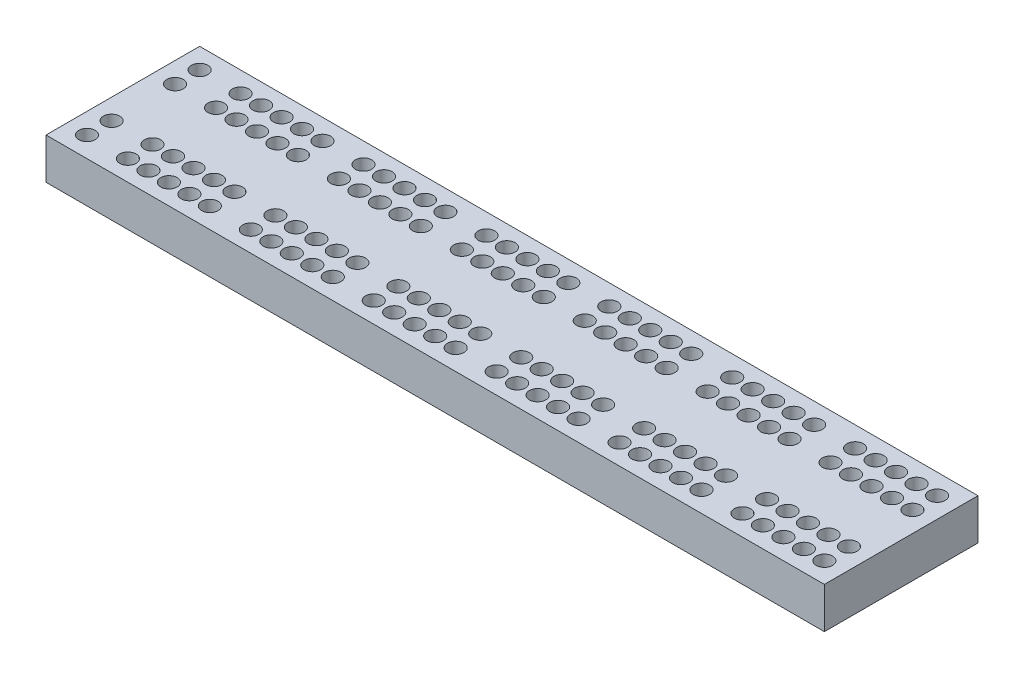
SolidWorks part; units mm, degrees
ref_plane "Front Plane" through (0, 0, 0) normal (0, 0, 1) x (1, 0, 0)
ref_plane "Top Plane" through (0, 0, 0) normal (0, 1, 0) x (1, 0, 0)
ref_plane "Right Plane" through (0, 0, 0) normal (1, 0, 0) x (0, 0, -1)
sketch "Sketch1" plane through (0, 0, 0) normal (1, 0, 0) x (0, 0, -1)
  line L1 (-37.5, 10) -> (37.5, 10)
  line L2 (-37.5, 10) -> (-37.5, -10)
  line L3 (-37.5, -10) -> (37.5, -10)
  line L4 (37.5, 10) -> (37.5, -10)
  line L5 (-37.5, 10) -> (37.5, -10) construction
  line L6 (-37.5, -10) -> (37.5, 10) construction
  point P0 (0, 0)
  dimension "D1" = 20
  dimension "D2" = 75
extrude "Boss-Extrude1" add sketch "Sketch1" along normal mid plane 380
hole_wizard "Ø8.0 (8) Diameter Hole1" positions "Sketch3" profile "Sketch2" hole size "Ø8.0" standard "ANSI Metric"
sketch "Sketch3" plane through (0, 10, 0) normal (0, 1, 0) x (1, 0, 0)
  line L0 (190, 37.5) -> (-190, 37.5) construction
  line L1 (-190, 37.5) -> (-190, -37.5) construction
  point P0 (-180, 27.5)
  dimension "D1" = 10
  dimension "D2" = 10
sketch "Sketch2" plane through (-180, 10, -27.5) normal (1, 0, 0) x (0, 0, 1)
  line L0 (0, 0) -> (0, 14.4034)
  line L1 (0, 14.4034) -> (4, 12)
  line L2 (4, 12) -> (4, 0)
  line L5 (4, 0) -> (0, 0)
  line L10 (0, 14.4034) -> (-4, 12) construction
  line L11 (0, -6.35) -> (0, 107.95) construction
  dimension "Hole Dia." = 8
  dimension "Hole Depth" = 12
  dimension "Drill Angle" = 118
pattern_linear "LPattern1" count 37 spacing 10 along (1, 0, 0) count 2 spacing 12 along (0, 0, 1) skipping (1, 0), (1, 1), (7, 0), (7, 1), (13, 0), (13, 1), (19, 0), (19, 1), (25, 0), (25, 1), (31, 0), (31, 1) of "Ø8.0 (8) Diameter Hole1"
mirror "Mirror1" about plane through (0, 0, 0) normal (0, 0, 1) of "LPattern1", "Ø8.0 (8) Diameter Hole1"
